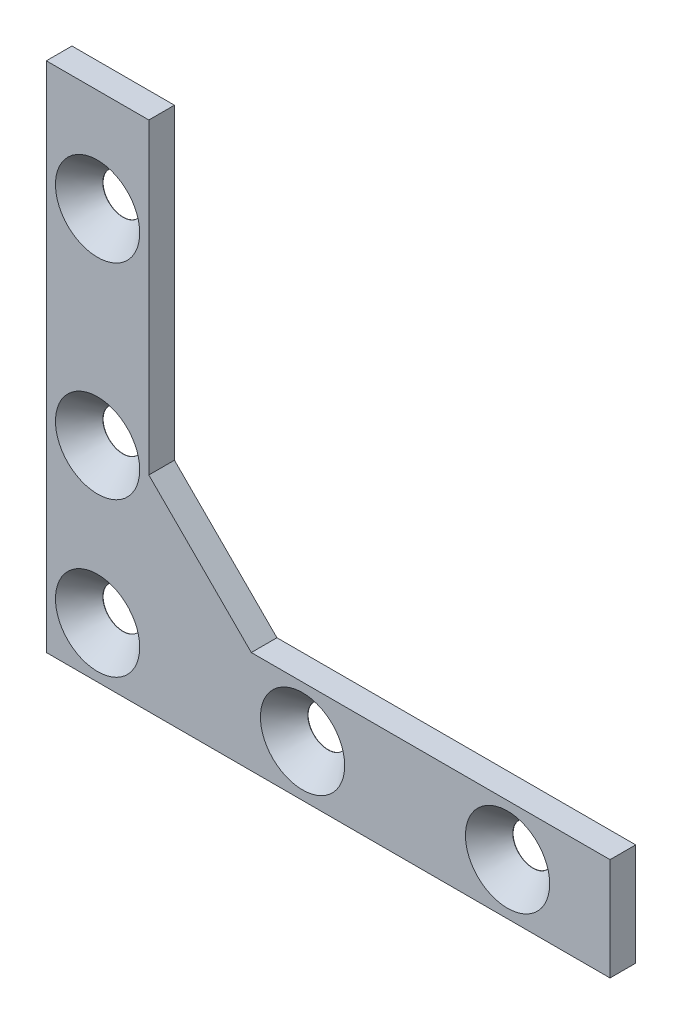
SolidWorks part; units mm, degrees
material "6061 Alloy"
ref_plane "Front Plane" through (0, 0, 0) normal (0, 0, 1) x (1, 0, 0)
ref_plane "Top Plane" through (0, 0, 0) normal (0, 1, 0) x (1, 0, 0)
ref_plane "Right Plane" through (0, 0, 0) normal (1, 0, 0) x (0, 0, -1)
sketch "Sketch1" plane through (0, 0, 0) normal (0, 0, 1) x (1, 0, 0)
  line L0 (-260.7534, 0) -> (-273.4534, 0)
  line L1 (-273.4534, 0) -> (-273.4534, 63.5)
  line L2 (-273.4534, 63.5) -> (-260.7534, 63.5)
  line L4 (-260.7534, 0) -> (-203.6034, 0)
  line L6 (-203.6034, 0) -> (-203.6034, 12.7)
  line L7 (-254, 12.7) -> (254, 12.7) construction
  line L8 (-203.6034, 12.7) -> (-248.0534, 12.7)
  line L9 (-248.0534, 12.7) -> (-260.7534, 25.4)
  line L10 (-260.7534, 25.4) -> (-260.7534, 63.5)
  dimension "D1" = 63.5
  dimension "D2" = 12.7
  dimension "D3" = 57.15
  dimension "D4" = 44.45
  dimension "D5" = 12.7
  dimension "D6" = 38.1
  dimension "D7" = 12.7
extrude "Boss-Extrude1" add sketch "Sketch1" along normal blind 3.175
sketch "Sketch2" plane through (0, 0, 3.175) normal (0, 0, 1) x (1, 0, 0)
  line L0 (-267.1034, 63.5) -> (-267.1034, 50.8) construction
  line L1 (-260.7534, 63.5) -> (-273.4534, 63.5) construction
  line L2 (-267.1034, 50.8) -> (-267.1034, 25.4) construction
  line L3 (-267.1034, 6.35) -> (-241.7034, 6.35) construction
  line L4 (-267.1034, 25.4) -> (-267.1034, 6.35) construction
  line L5 (-241.7034, 6.35) -> (-216.3034, 6.35) construction
  line L6 (-203.6034, 6.35) -> (-216.3034, 6.35) construction
  line L7 (-203.6034, 0) -> (-203.6034, 12.7) construction
  dimension "D1" = 19.05
  dimension "D2" = 25.4
  dimension "D3" = 25.4
  dimension "D4" = 25.4
hole_wizard "#10 Clearance Hole1" positions "Sketch3" profile "Sketch4" hole size "#10" standard "ANSI Inch" end condition through all
sketch "Sketch3" plane through (0, 0, 3.175) normal (0, 0, 1) x (1, 0, 0)
  point P0 (-267.1034, 6.35)
  point P3 (-267.1034, 25.4)
  point P6 (-267.1034, 50.8)
  point P9 (-241.7034, 6.35)
  point P12 (-216.3034, 6.35)
sketch "Sketch4" plane through (-267.1034, 6.35, 3.175) normal (1, 0, 0) x (0, -1, 0)
  line L0 (0, 0) -> (0, 3.175)
  line L1 (0, 3.175) -> (2.4892, 3.175)
  line L2 (2.4892, 3.175) -> (2.4892, 3.1411)
  line L3 (2.4892, 3.1411) -> (5.2197, 0)
  line L5 (5.2197, 0) -> (0, 0)
  line L6 (-2.4892, 3.1411) -> (-5.2197, 0) construction
  line L11 (0, -6.35) -> (0, 107.95) construction
  dimension "Thru Hole Dia." = 4.9784
  dimension "Thru Hole Depth" = 3.175
  dimension "Near C'Sink Dia." = 10.4394
  dimension "Near C'Sink Angle" = 82
